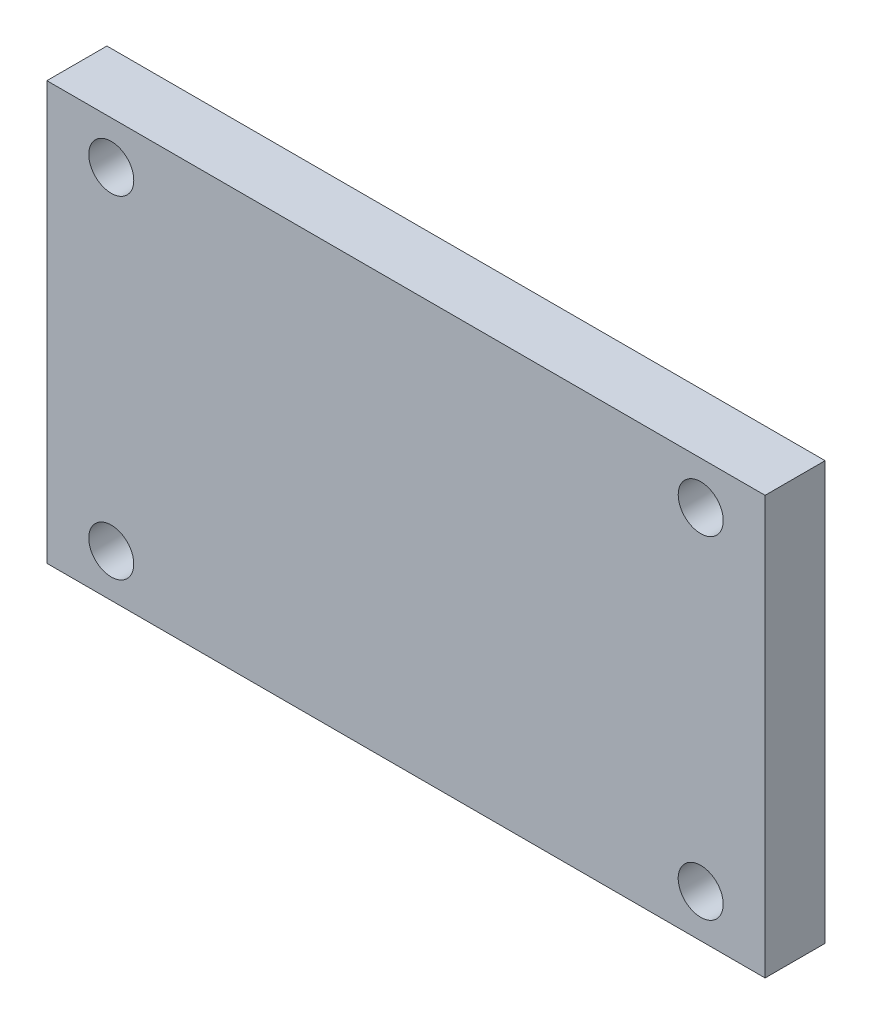
SolidWorks part; units mm, degrees
ref_plane "前视基准面" through (0, 0, 0) normal (0, 0, 1) x (1, 0, 0)
ref_plane "上视基准面" through (0, 0, 0) normal (0, 1, 0) x (1, 0, 0)
ref_plane "右视基准面" through (0, 0, 0) normal (1, 0, 0) x (0, 0, -1)
sketch "草图1" plane through (0, 0, 0) normal (0, 0, 1) x (1, 0, 0)
  line L0 (16.7515, 0) -> (16.7515, -19.5) construction
  line L1 (0, 0) -> (33.503, 0)
  line L2 (0, 0) -> (0, -19.5)
  line L3 (0, -19.5) -> (33.503, -19.5)
  line L4 (33.503, 0) -> (33.503, -19.5)
  line L5 (0, -9.75) -> (33.503, -9.75) construction
  circle A0 centre (3.003, -2) radius 1.05
  circle A1 centre (3.003, -17.5) radius 1.05
  circle A2 centre (30.5, -17.5) radius 1.05
  circle A3 centre (30.5, -2) radius 1.05
  dimension "D4" = 2.1
  dimension "D5" = 7.75
  dimension "D1" = 33.503
  dimension "D2" = 19.5
  dimension "D3" = 13.7485
extrude "凸台-拉伸1" add sketch "草图1" along normal blind 2.8
